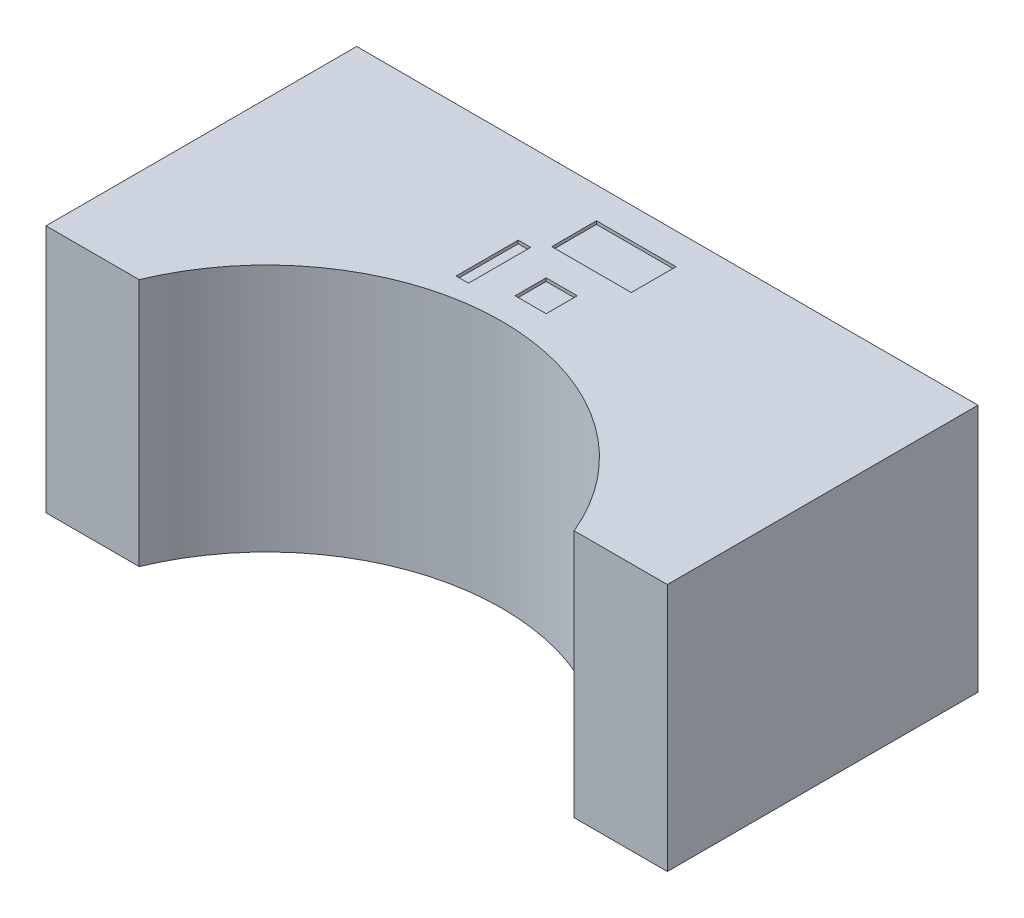
SolidWorks part; units mm, degrees
ref_plane "前视基准面" through (0, 0, 0) normal (0, 0, 1) x (1, 0, 0)
ref_plane "上视基准面" through (0, 0, 0) normal (0, 1, 0) x (1, 0, 0)
ref_plane "右视基准面" through (0, 0, 0) normal (1, 0, 0) x (0, 0, -1)
sketch "草图1" plane through (0, 0, 0) normal (0, 1, 0) x (1, 0, 0)
  line L0 (0, 0) -> (500, 0)
  line L1 (0, 0) -> (-500, 0)
  line L2 (-500, 0) -> (-500, -500)
  line L3 (-500, -500) -> (-350, -500)
  line L4 (500, 0) -> (500, -500)
  line L5 (500, -500) -> (350, -500)
  arc A0 (-350, -500) -> (350, -500) centre (0, -644.9747) cw
  dimension "D1" = 1000
  dimension "D2" = 500
  dimension "D3" = 500
  dimension "D4" = 150
  dimension "D5" = 150
extrude "凸台-拉伸1" add sketch "草图1" along normal blind 400
sketch "草图2" plane through (0, 400, 0) normal (0, 1, 0) x (1, 0, 0)
  line L0 (-64, -50) -> (64, -50)
  line L1 (500, 0) -> (-500, 0) construction
  line L2 (-500, 0) -> (-500, -500) construction
  line L3 (500, -500) -> (500, 0) construction
  line L4 (-64, -50) -> (-64, -122)
  line L5 (-64, -122) -> (64, -122)
  line L6 (64, -122) -> (64, -50)
  dimension "D1" = 50
  dimension "D2" = 436
  dimension "D3" = 436
  dimension "D4" = 72
extrude "切除-拉伸1" cut sketch "草图2" against normal blind 5
sketch "草图3" plane through (0, 400, 0) normal (0, 1, 0) x (1, 0, 0)
  line L0 (500, 0) -> (-500, 0) construction
  line L1 (-25, -170) -> (25, -170)
  line L2 (-25, -170) -> (-25, -220)
  line L3 (-25, -220) -> (25, -220)
  line L4 (25, -170) -> (25, -220)
  line L5 (-500, 0) -> (-500, -500) construction
  dimension "D1" = 50
  dimension "D2" = 50
  dimension "D3" = 170
  dimension "D4" = 475
extrude "切除-拉伸3" cut sketch "草图3" against normal blind 5
sketch "草图4" plane through (0, 400, 0) normal (0, 1, 0) x (1, 0, 0)
  line L0 (-500, 0) -> (-500, -500) construction
  line L1 (-100, -140) -> (-80, -140)
  line L2 (-100, -140) -> (-100, -240)
  line L3 (-100, -240) -> (-80, -240)
  line L4 (-80, -140) -> (-80, -240)
  line L5 (500, 0) -> (-500, 0) construction
  dimension "D1" = 100
  dimension "D2" = 20
  dimension "D3" = 400
  dimension "D4" = 140
extrude "切除-拉伸4" cut sketch "草图4" against normal blind 5
